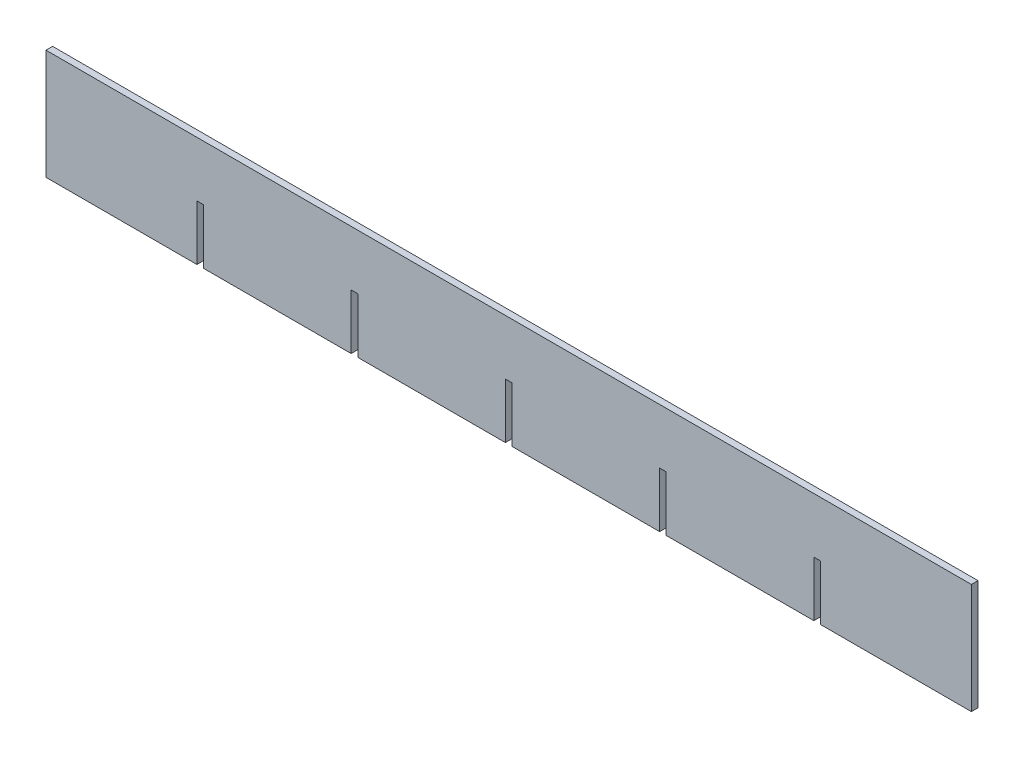
SolidWorks part; units mm, degrees
ref_plane "Front Plane" through (0, 0, 0) normal (0, 0, 1) x (1, 0, 0)
ref_plane "Top Plane" through (0, 0, 0) normal (0, 1, 0) x (1, 0, 0)
ref_plane "Right Plane" through (0, 0, 0) normal (1, 0, 0) x (0, 0, -1)
sketch "Sketch1" plane through (0, 0, 0) normal (0, 0, 1) x (1, 0, 0)
  line L1 (0, 0) -> (420, 0)
  line L2 (0, 0) -> (0, 50)
  line L3 (0, 50) -> (420, 50)
  line L4 (420, 0) -> (420, 50)
  line L5 (68.5, 0) -> (71.5, 0)
  line L6 (68.5, 0) -> (68.5, 25)
  line L7 (68.5, 25) -> (71.5, 25)
  line L8 (71.5, 0) -> (71.5, 25)
  line L9 (138.5, 0) -> (141.5, 0)
  line L10 (138.5, 0) -> (138.5, 25)
  line L11 (138.5, 25) -> (141.5, 25)
  line L12 (141.5, 0) -> (141.5, 25)
  line L13 (208.5, 0) -> (211.5, 0)
  line L14 (208.5, 0) -> (208.5, 25)
  line L15 (208.5, 25) -> (211.5, 25)
  line L16 (211.5, 0) -> (211.5, 25)
  line L17 (278.5, 0) -> (281.5, 0)
  line L18 (278.5, 0) -> (278.5, 25)
  line L19 (278.5, 25) -> (281.5, 25)
  line L20 (281.5, 0) -> (281.5, 25)
  line L21 (348.5, 0) -> (351.5, 0)
  line L22 (348.5, 0) -> (348.5, 25)
  line L23 (348.5, 25) -> (351.5, 25)
  line L24 (351.5, 0) -> (351.5, 25)
  point P25 (70, 25)
  point P26 (140, 25)
  point P27 (210, 25)
  point P28 (280, 25)
  point P29 (350, 25)
  dimension "D1" = 50
  dimension "D2" = 420
  dimension "D3" = 70
  dimension "D4" = 25
  dimension "D5" = 3
  dimension "D6" = 3
  dimension "D7" = 3
  dimension "D8" = 3
  dimension "D9" = 3
  dimension "D10" = 25
  dimension "D11" = 25
  dimension "D12" = 25
  dimension "D13" = 25
  dimension "D14" = 140
  dimension "D15" = 210
  dimension "D16" = 280
  dimension "D17" = 350
extrude "Boss-Extrude1" add sketch "Sketch1" along normal blind 3 contours L24 L1 L4 L3 L2 L6 L7 L8 L10 L11 L12 L14 L15 L16 L18 L19 L20 L22 L23
